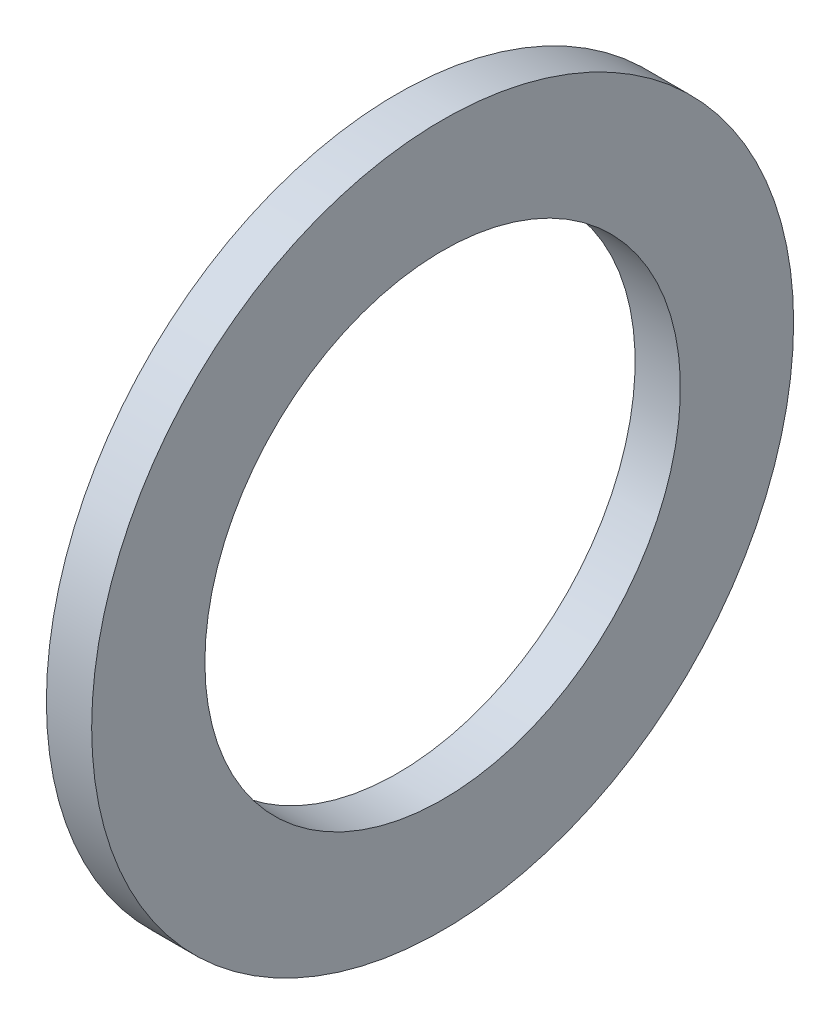
SolidWorks part; units mm, degrees
ref_plane "Plane1" through (0, 0, 0) normal (0, 0, 1) x (1, 0, 0)
ref_plane "Plane2" through (0, 0, 0) normal (0, 1, 0) x (1, 0, 0)
ref_plane "Plane3" through (0, 0, 0) normal (1, 0, 0) x (0, 0, -1)
sketch "Sketch1" plane through (0, 0, 0) normal (0, 0, 1) x (1, 0, 0)
  line L0 (-34.925, 0) -> (9.525, 0) construction
  line L1 (0, 10.5) -> (0, 15.5)
  line L2 (0, 15.5) -> (-2, 15.5)
  line L3 (-2, 15.5) -> (-2, 10.5)
  line L4 (-2, 10.5) -> (0, 10.5)
  dimension "Thickness" = 2
  dimension "Inside_dia" = 21
  dimension "Outside_dia" = 31
revolve "Base-Revolve" add sketch "Sketch1" angle 360 about L0
